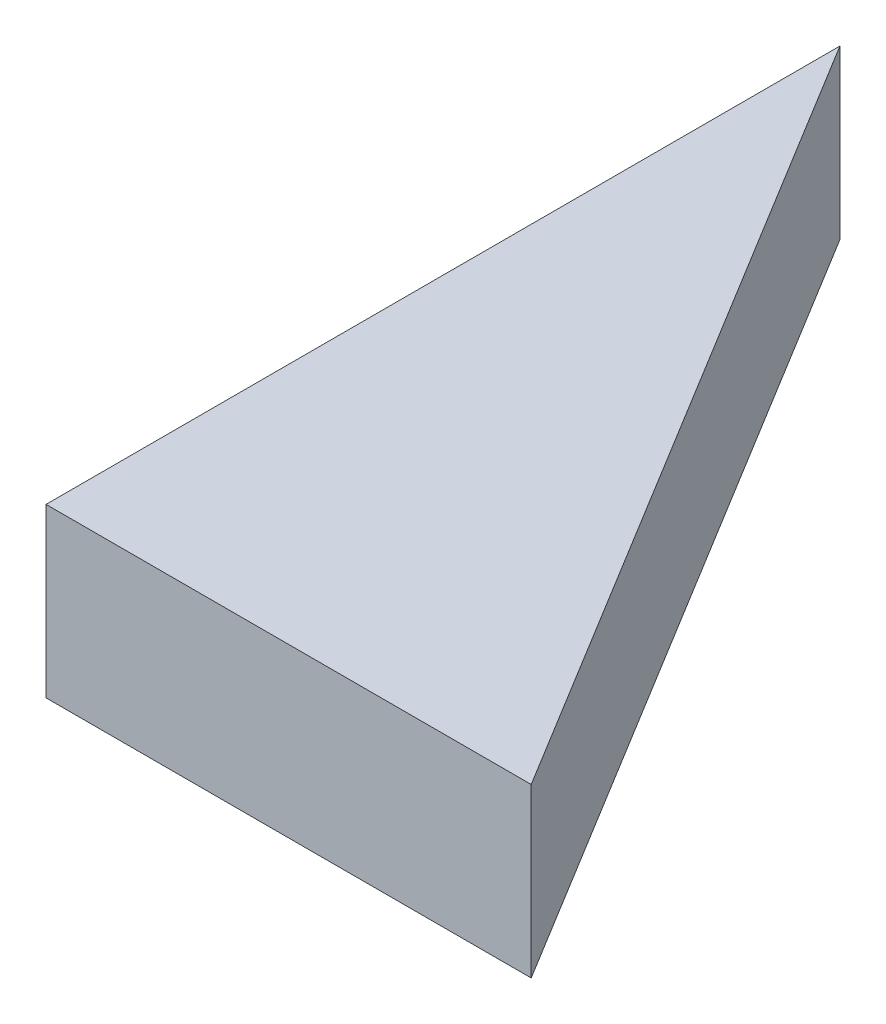
SolidWorks part; units mm, degrees
material "Polyurethane Foam Flexible"
ref_plane "Front Plane" through (0, 0, 0) normal (0, 0, 1) x (1, 0, 0)
ref_plane "Top Plane" through (0, 0, 0) normal (0, 1, 0) x (1, 0, 0)
ref_plane "Right Plane" through (0, 0, 0) normal (1, 0, 0) x (0, 0, -1)
sketch "Sketch1" plane through (0, 0, 0) normal (0, 1, 0) x (1, 0, 0)
  line L0 (0, 0) -> (139.7, 0)
  line L1 (139.7, 0) -> (0, 228.6)
  line L2 (0, 228.6) -> (0, 0)
  dimension "D1" = 228.6
  dimension "D2" = 139.7
extrude "Boss-Extrude1" add sketch "Sketch1" along normal blind 48.26
